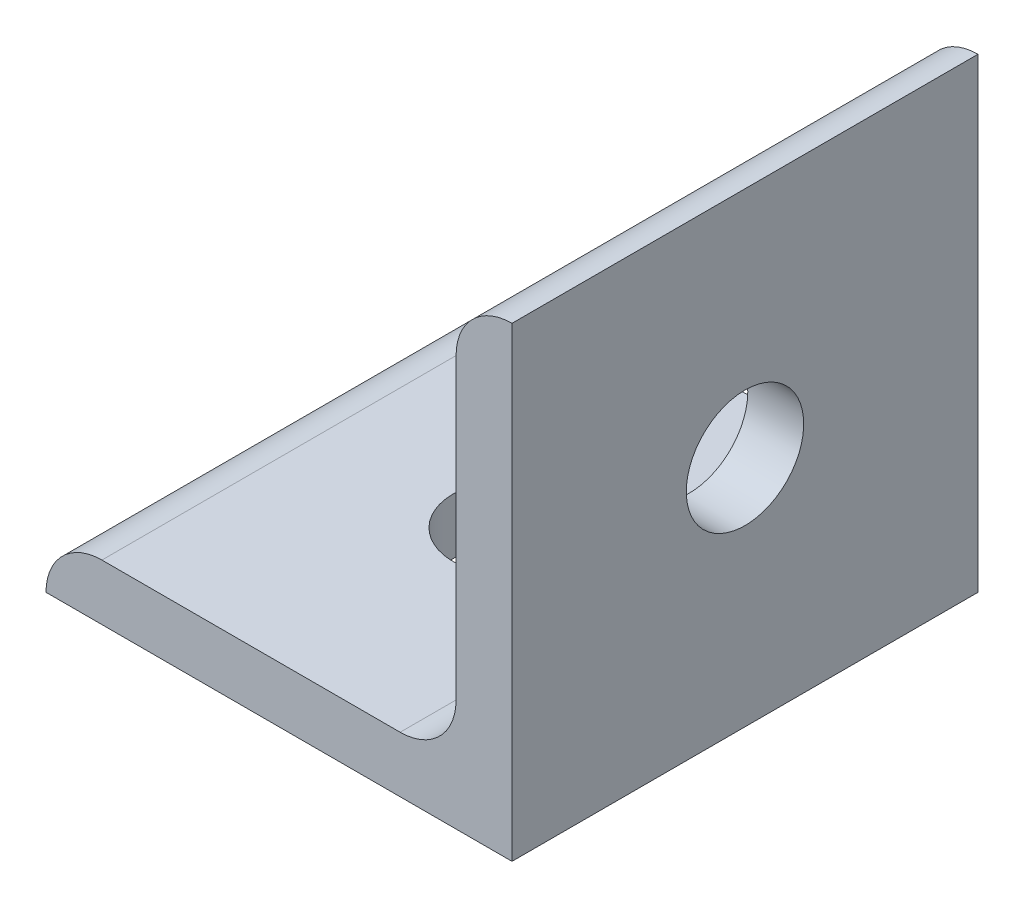
SolidWorks part; units mm, degrees
ref_plane "Front Plane" through (0, 0, 0) normal (0, 0, 1) x (1, 0, 0)
ref_plane "Top Plane" through (0, 0, 0) normal (0, 1, 0) x (1, 0, 0)
ref_plane "Right Plane" through (0, 0, 0) normal (1, 0, 0) x (0, 0, -1)
sketch "Sketch1" plane through (0, 0, 0) normal (0, 0, 1) x (1, 0, 0)
  line L0 (22.3963, -5.4589) -> (22.3963, -30.4589)
  line L1 (22.3963, -30.4589) -> (-2.6037, -30.4589)
  line L2 (19.3963, -8.4589) -> (19.3963, -24.4589)
  line L3 (16.3963, -27.4589) -> (0.3963, -27.4589)
  line L4 (19.3963, -27.4589) -> (-2.6037, -27.4589) construction
  line L5 (19.3963, -5.4589) -> (19.3963, -27.4589) construction
  arc A0 (0.3963, -27.4589) -> (-2.6037, -30.4589) centre (0.3963, -30.4589) ccw
  arc A1 (22.3963, -5.4589) -> (19.3963, -8.4589) centre (22.3963, -8.4589) ccw
  arc A2 (16.3963, -27.4589) -> (19.3963, -24.4589) centre (16.3963, -24.4589) ccw
  dimension "D4" = 3
  dimension "D1" = 25
  dimension "D2" = 25
  dimension "D3" = 3
extrude "Extrude1" add sketch "Sketch1" along normal blind 25
sketch "Sketch2" plane through (22.3963, 0, 0) normal (1, 0, 0) x (0, 0, -1)
  circle A0 centre (-12.5, -17.9589) radius 3.15
extrude "Cut-Extrude1" cut sketch "Sketch2" against normal blind 25
sketch "Sketch3" plane through (0, -30.4589, 0) normal (0, -1, 0) x (1, 0, 0)
  circle A0 centre (9.8963, 12.5) radius 3.15
extrude "Cut-Extrude2" cut sketch "Sketch3" against normal blind 25
